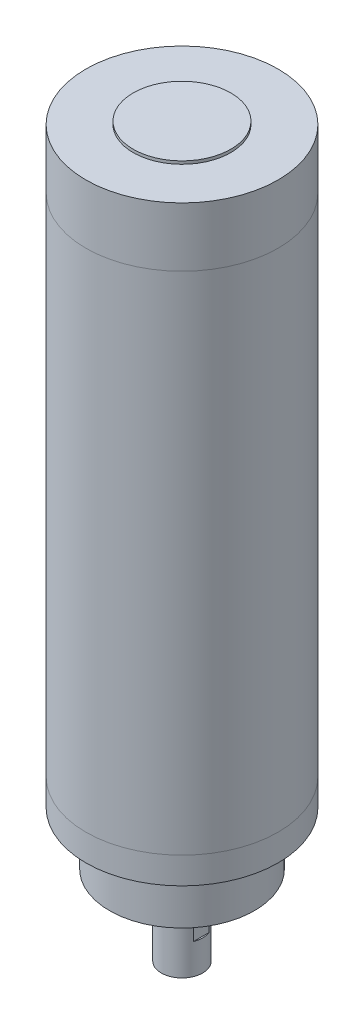
SolidWorks part; units mm, degrees
ref_plane "Спереди" through (0, 0, 0) normal (0, 0, 1) x (1, 0, 0)
ref_plane "Сверху" through (0, 0, 0) normal (0, 1, 0) x (1, 0, 0)
ref_plane "Справа" through (0, 0, 0) normal (1, 0, 0) x (0, 0, -1)
sketch "Эскиз1" plane through (0, 0, 0) normal (0, 1, 0) x (1, 0, 0)
  circle A0 centre (0, 0) radius 32.5
  dimension "D1" = 65
extrude "Бобышка-Вытянуть1" add sketch "Эскиз1" along normal blind 171
sketch "Эскиз6" plane through (0, 0, 0) normal (0, 0, 1) x (1, 0, 0)
  line L0 (0, 0) -> (0, -27)
  line L1 (0, -27) -> (24.5, -27)
  line L2 (24.5, -27) -> (24.5, -9)
  line L3 (24.5, -9) -> (32.5, -9)
  line L4 (32.5, -9) -> (32.5, 0)
  line L5 (32.5, 0) -> (0, 0)
  line L6 (0, 171) -> (0, 192)
  line L7 (32.5, 171) -> (-32.5, 171) construction
  line L8 (0, 192) -> (16.5, 192)
  line L9 (16.5, 192) -> (16.5, 191)
  line L10 (16.5, 191) -> (32.5, 191)
  line L11 (32.5, 191) -> (32.5, 171)
  line L12 (32.5, 171) -> (0, 171)
  dimension "D1" = 9
  dimension "D2" = 18
  dimension "D3" = 24.5
  dimension "D4" = 200
  dimension "D5" = 16.5
  dimension "D6" = 1
revolve "Повернуть1" add sketch "Эскиз6" angle 360 about L0
sketch "Эскиз7" plane through (0, 0, 0) normal (0, 0, 1) x (1, 0, 0)
  line L0 (0, -27) -> (0, -29.5)
  line L1 (-24.5, -27) -> (24.5, -27) construction
  line L2 (0, -29.5) -> (14.75, -29.5)
  line L3 (14.75, -29.5) -> (14.75, -27)
  line L4 (14.75, -27) -> (0, -27)
  dimension "D1" = 14.75
  dimension "D2" = 2.5
revolve "Повернуть2" add sketch "Эскиз7" angle 360 about L0
sketch "Эскиз8" plane through (0, 0, 0) normal (0, 0, 1) x (1, 0, 0)
  line L0 (7.5, -29.5) -> (7.5, -32)
  line L1 (-14.75, -29.5) -> (14.75, -29.5) construction
  line L2 (7.5, -32) -> (7, -32)
  line L3 (7, -32) -> (7, -54)
  line L4 (7, -54) -> (5.5, -54)
  line L5 (5.5, -54) -> (3.6027, -40.5)
  line L6 (3.6027, -40.5) -> (0, -40.5)
  line L7 (0, -40.5) -> (0, -29.5)
  line L8 (0, -29.5) -> (7.5, -29.5)
  dimension "D1" = 7.5
  dimension "D2" = 7
  dimension "D3" = 8
  dimension "D4" = 5.5
  dimension "D5" = 24.5
  dimension "D6" = 22
  dimension "D7" = 13.5
revolve "Повернуть3" add sketch "Эскиз8" angle 360 about L7
sketch "Эскиз9" plane through (0, 0, 0) normal (0, 0, 1) x (1, 0, 0)
  line L0 (7, -54) -> (7, -32) construction
  line L1 (7, -35.5) -> (6.5, -35.5)
  line L2 (7, -35.5) -> (7, -43.7)
  line L3 (7, -43.7) -> (6.5, -43.7)
  line L4 (6.5, -35.5) -> (6.5, -43.7)
  line L5 (-7, -54) -> (7, -54) construction
  dimension "D1" = 6.5
  dimension "D2" = 10.3
  dimension "D3" = 18.5
extrude "Вырез-Вытянуть1" cut sketch "Эскиз9" against normal through all both and the other way through all
mirror "Зеркальное отражение1" about plane through (0, 0, 0) normal (1, 0, 0) of "Вырез-Вытянуть1"
chamfer "Фаска1" distance 0.5 angle 45 1 edges at (5.5, -54, 0)
